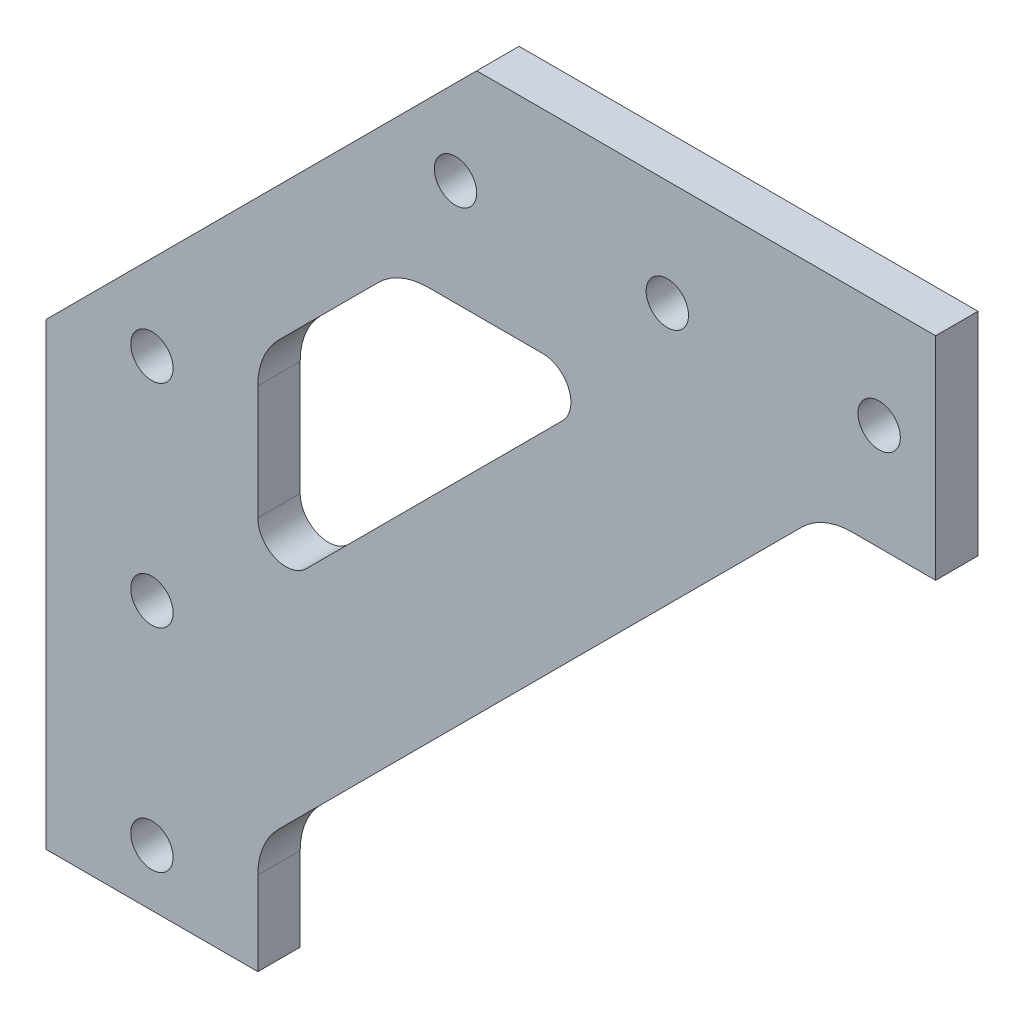
SolidWorks part; units mm, degrees
material "S-玻璃纤维"
ref_plane "前视基准面" through (0, 0, 0) normal (0, 0, 1) x (1, 0, 0)
ref_plane "上视基准面" through (0, 0, 0) normal (0, 1, 0) x (1, 0, 0)
ref_plane "右视基准面" through (0, 0, 0) normal (1, 0, 0) x (0, 0, -1)
sketch "草图1" plane through (0, 0, 0) normal (0, 0, 1) x (1, 0, 0)
  line L5 (32.5, 0) -> (32.5, -15)
  line L6 (32.5, -15) -> (26.5711, -15)
  line L7 (23.0355, -16.4645) -> (-14.0355, -53.5355)
  line L8 (-15.5, -57.0711) -> (-15.5, -63)
  line L9 (-15.5, -63) -> (-30.5, -63)
  line L12 (-12.0858, -36.5858) -> (6.0858, -18.4142)
  line L15 (4.6716, -15) -> (-3.4289, -15)
  line L18 (0, 0) -> (32.5, 0)
  line L19 (-15.5, -35.1716) -> (-15.5, -27.0711)
  line L21 (-30.5, -30.5) -> (-30.5, -63)
  line L22 (-6.9645, -16.4645) -> (-14.0355, -23.5355)
  line L23 (-30.5, -30.5) -> (0, 0)
  arc A0 (-15.5, -35.1716) -> (-12.0858, -36.5858) centre (-13.5, -35.1716) ccw
  arc A1 (6.0858, -18.4142) -> (4.6716, -15) centre (4.6716, -17) ccw
  arc A2 (-3.4289, -15) -> (-6.9645, -16.4645) centre (-3.4289, -20) ccw
  arc A3 (-15.5, -27.0711) -> (-14.0355, -23.5355) centre (-10.5, -27.0711) cw
  arc A4 (26.5711, -15) -> (23.0355, -16.4645) centre (26.5711, -20) ccw
  arc A5 (-14.0355, -53.5355) -> (-15.5, -57.0711) centre (-10.5, -57.0711) ccw
  point P5 (-15.5, -40)
  point P18 (9.5, -15)
  point P21 (-5.5, -15)
  point P26 (24.5, -15)
  point P29 (-15.5, -55)
  dimension "D10" = 2
  dimension "D11" = 5
  dimension "D12" = 5
  dimension "D1" = 15
  dimension "D2" = 32.5
  dimension "D3" = 8
  dimension "D4" = 15
  dimension "D5" = 15
  dimension "D6" = 135
  dimension "D7" = 40
  dimension "D8" = 15
  dimension "D9" = 15
extrude "凸台-拉伸1" add sketch "草图1" along normal blind 3
sketch "草图2" plane through (0, 0, 3) normal (0, 0, 1) x (1, 0, 0)
  line L0 (32.5, 0) -> (0, 0) construction
  line L1 (-30.5, -30.5) -> (-30.5, -63) construction
  line L2 (32.5, -15) -> (32.5, 0) construction
  line L3 (-30.5, -63) -> (-15.5, -63) construction
  circle A0 centre (28.5, -7.5) radius 1.5
  circle A1 centre (13.5, -7.5) radius 1.5
  circle A2 centre (-1.5, -7.5) radius 1.5
  circle A3 centre (-23, -29) radius 1.5
  circle A4 centre (-23, -44) radius 1.5
  circle A5 centre (-23, -59) radius 1.5
  dimension "D1" = 3
  dimension "D2" = 7.5
  dimension "D3" = 7.5
  dimension "D4" = 4
  dimension "D5" = 15
  dimension "D6" = 15
  dimension "D7" = 4
  dimension "D8" = 15
  dimension "D9" = 15
extrude "切除-拉伸1" cut sketch "草图2" against normal blind 10
